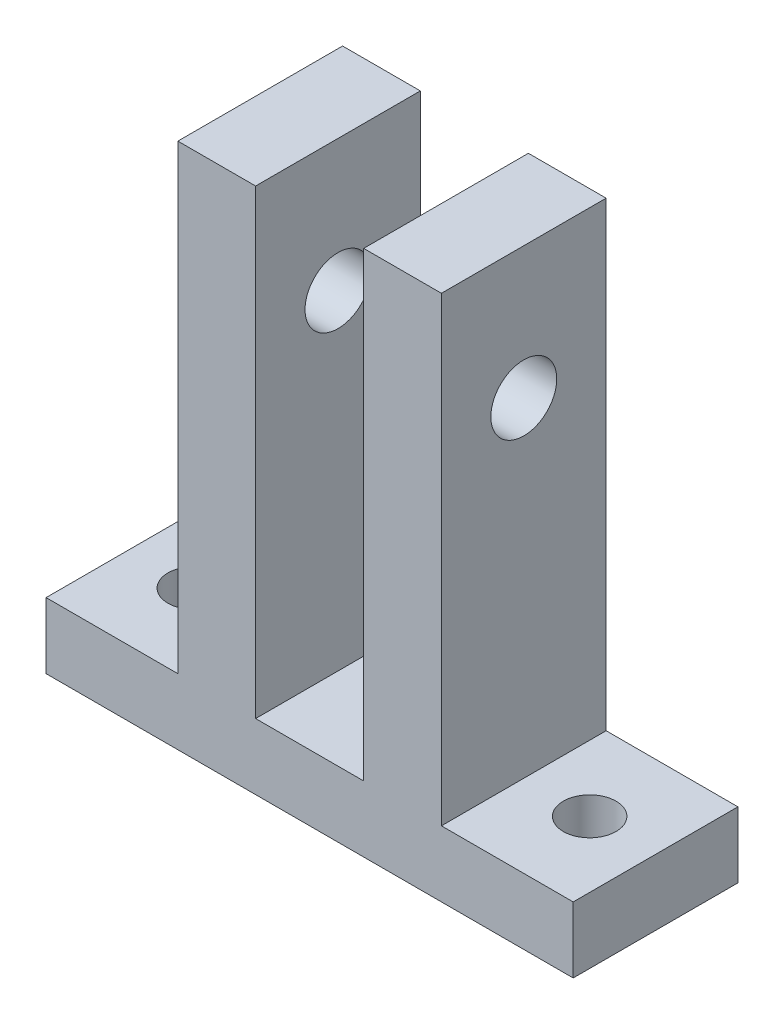
SolidWorks part; units mm, degrees
ref_plane "Спереди" through (0, 0, 0) normal (0, 0, 1) x (1, 0, 0)
ref_plane "Сверху" through (0, 0, 0) normal (0, 1, 0) x (1, 0, 0)
ref_plane "Справа" through (0, 0, 0) normal (1, 0, 0) x (0, 0, -1)
sketch "Эскиз1" plane through (0, 0, 0) normal (0, 0, 1) x (1, 0, 0)
  line L0 (0, 0) -> (0, 5)
  line L1 (0, 5) -> (10, 5)
  line L2 (10, 5) -> (10, 40)
  line L3 (10, 40) -> (15.9, 40)
  line L4 (15.9, 40) -> (15.9, 5)
  line L5 (15.9, 5) -> (24.1, 5)
  line L6 (24.1, 5) -> (24.1, 40)
  line L7 (24.1, 40) -> (30, 40)
  line L8 (30, 40) -> (30, 5)
  line L9 (30, 5) -> (40, 5)
  line L10 (40, 5) -> (40, 0)
  line L11 (40, 0) -> (0, 0)
  dimension "D1" = 20
  dimension "D2" = 40
  dimension "D3" = 8.2
  dimension "D4" = 5
  dimension "D5" = 35
extrude "Вытянуть1" add sketch "Эскиз1" along normal blind 12.5
sketch "Эскиз2" plane through (10, 0, 0) normal (-1, 0, 0) x (0, 0, 1)
  line L0 (12.5, 40) -> (0, 40) construction
  circle A0 centre (6.25, 30) radius 2.5
  point P4 (6.25, 40)
  dimension "D1" = 5
  dimension "D2" = 10
extrude "Вытянуть2" cut sketch "Эскиз2" against normal through all
sketch "Эскиз3" plane through (0, 5, 0) normal (0, 1, 0) x (1, 0, 0)
  line L0 (40, -12.5) -> (30, -12.5) construction
  line L1 (40, -12.5) -> (40, 0) construction
  line L2 (10, -12.5) -> (0, -12.5) construction
  circle A0 centre (35, -6.25) radius 2
  circle A1 centre (5, -6.25) radius 2
  point P0 (35, -12.5)
  point P1 (40, -6.25)
  point P4 (5, -12.5)
  dimension "D1" = 4
extrude "Вытянуть3" cut sketch "Эскиз3" against normal up to next
